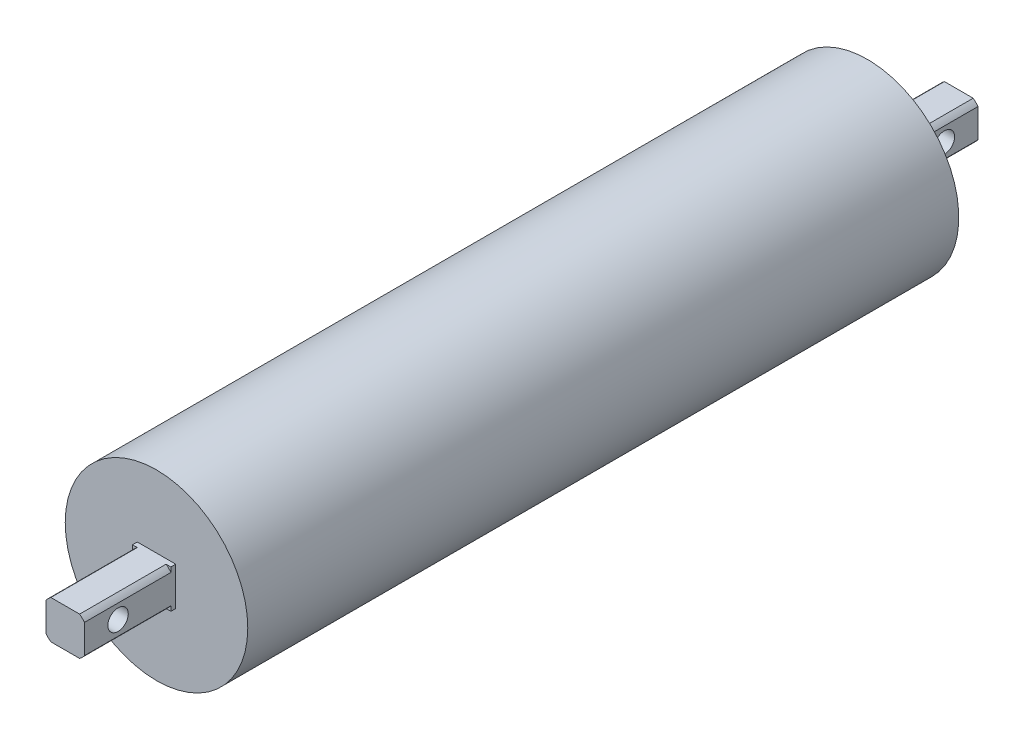
SolidWorks part; units mm, degrees
material "45钢"
ref_plane "前视基准面" through (0, 0, 0) normal (0, 0, 1) x (1, 0, 0)
ref_plane "上视基准面" through (0, 0, 0) normal (0, 1, 0) x (1, 0, 0)
ref_plane "右视基准面" through (0, 0, 0) normal (1, 0, 0) x (0, 0, -1)
sketch "草图1" plane through (0, 0, 0) normal (0, 0, 1) x (1, 0, 0)
  circle A0 centre (0, 0) radius 38
  dimension "D1" = 76
extrude "凸台-拉伸1" add sketch "草图1" along normal mid plane 300
sketch "草图2" plane through (0, 0, 150) normal (0, 0, 1) x (1, 0, 0)
  circle A0 centre (0, 0) radius 10
  dimension "D1" = 20
extrude "凸台-拉伸2" add sketch "草图2" along normal blind 36
sketch "草图3" plane through (0, 0, 186) normal (0, 0, 1) x (1, 0, 0)
  line L1 (8, -8) -> (-8, -8)
  line L2 (8, -8) -> (8, 8)
  line L3 (8, 8) -> (-8, 8)
  line L4 (-8, -8) -> (-8, 8)
  line L5 (8, -8) -> (-8, 8) construction
  line L6 (8, 8) -> (-8, -8) construction
  point P0 (0, 0)
  dimension "D1" = 16
extrude "切除-拉伸1" cut sketch "草图3" against normal blind 38 flip side to cut
sketch "草图4" plane through (-8, 0, 0) normal (-1, 0, 0) x (0, 0, 1)
  line L0 (186, 0) -> (172, 0) construction
  line L1 (186, 6) -> (186, -6) construction
  point P6 (172, 0)
  dimension "D1" = 14
hole_wizard "M10 螺纹孔1" positions "草图4" profile "草图5" tap size "M10" standard "GB" end condition through all
sketch "草图5" plane through (-8, 0, 172) normal (0, 1, 0) x (0, 0, 1)
  line L0 (0, 0) -> (0, 46)
  line L1 (0, 46) -> (4.25, 46)
  line L2 (4.25, 46) -> (4.25, 0)
  line L5 (4.25, 0) -> (0, 0)
  line L11 (0, -6.35) -> (0, 107.95) construction
  dimension "通孔螺纹孔钻头直径" = 8.5
  dimension "通孔螺纹孔钻头深度" = 46
cosmetic thread "孔螺纹线1" parameters "D2"=10
mirror "镜向1" about plane through (0, 0, 0) normal (0, 0, 1) of "M10 螺纹孔1", "凸台-拉伸2", "切除-拉伸1"
